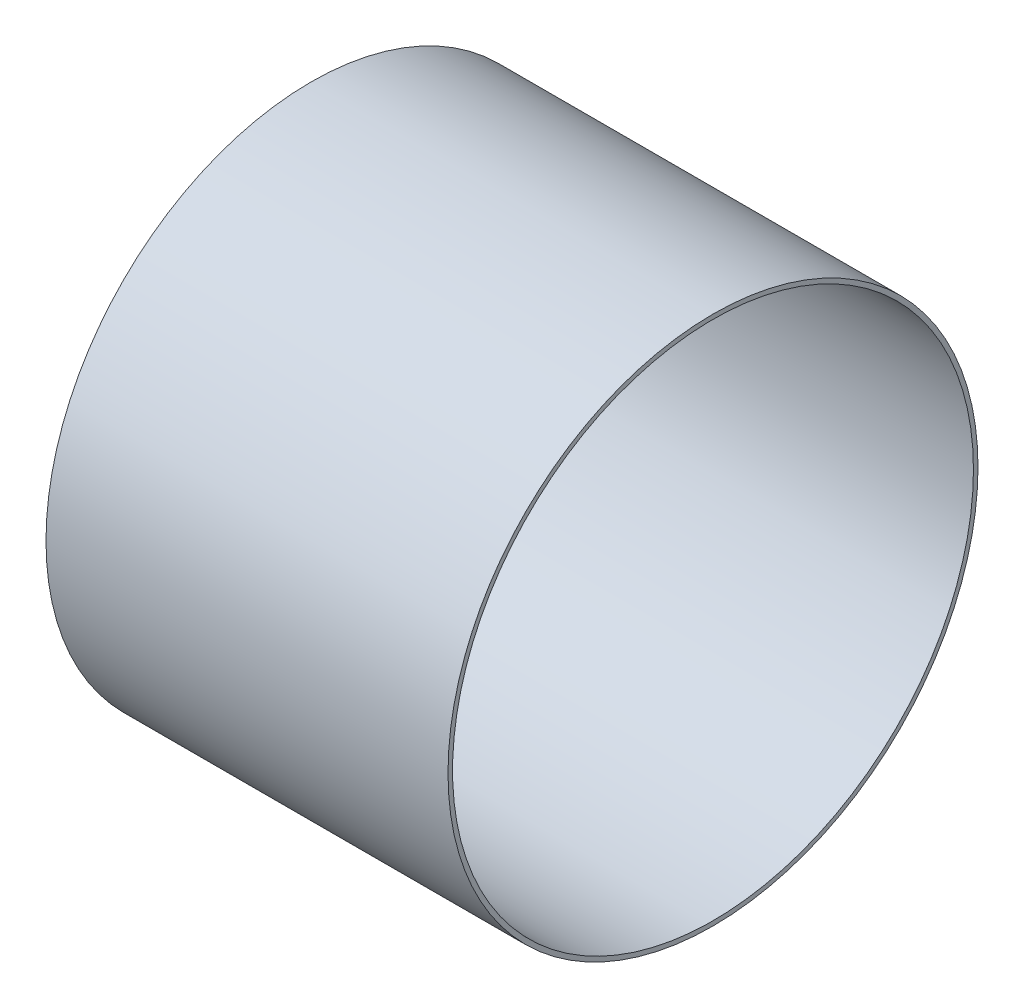
SolidWorks part; units mm, degrees
ref_plane "Front Plane" through (0, 0, 0) normal (0, 0, 1) x (1, 0, 0)
ref_plane "Top Plane" through (0, 0, 0) normal (0, 1, 0) x (1, 0, 0)
ref_plane "Right Plane" through (0, 0, 0) normal (1, 0, 0) x (0, 0, -1)
sketch "Sketch1" plane through (0, 0, 0) normal (1, 0, 0) x (0, 0, -1)
  circle A0 centre (0, 0) radius 48.8442
  circle A1 centre (0, 0) radius 48.006
  dimension "D1" = 0.8382
  dimension "D2" = 96.012
extrude "Boss-Extrude1" add sketch "Sketch1" along normal blind 74.0969
